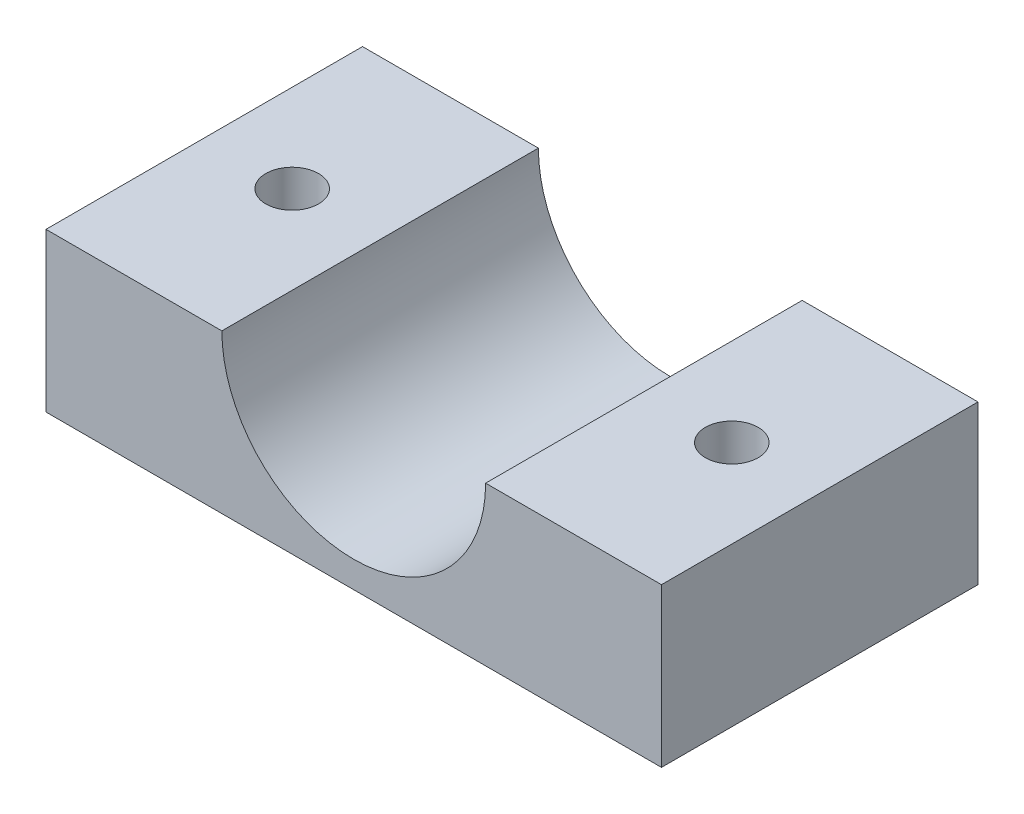
SolidWorks part; units mm, degrees
ref_plane "Front Plane" through (0, 0, 0) normal (0, 0, 1) x (1, 0, 0)
ref_plane "Top Plane" through (0, 0, 0) normal (0, 1, 0) x (1, 0, 0)
ref_plane "Right Plane" through (0, 0, 0) normal (1, 0, 0) x (0, 0, -1)
sketch "Sketch1" plane through (0, 0, 0) normal (0, 1, 0) x (1, 0, 0)
  line L0 (0, -1000) -> (0, 49000) construction
  line L1 (-17.5, -9) -> (17.5, -9)
  line L2 (-17.5, -9) -> (-17.5, 9)
  line L3 (-17.5, 9) -> (17.5, 9)
  line L4 (17.5, -9) -> (17.5, 9)
  line L5 (-17.5, -9) -> (17.5, 9) construction
  line L6 (-17.5, 9) -> (17.5, -9) construction
  line L7 (-1000, 0) -> (49000, 0) construction
  line L8 (7.5, -1000) -> (7.5, 49000) construction
  line L9 (-7.5, -1000) -> (-7.5, 49000) construction
  circle A0 centre (-12.5, 0) radius 1.5
  circle A1 centre (12.5, 0) radius 1.5
  point P0 (0, 0)
  dimension "D4" = 3
  dimension "D1" = 18
  dimension "D2" = 35
  dimension "D3" = 5
  dimension "D5" = 7.5
  dimension "D6" = 7.5
extrude "Boss-Extrude1" add sketch "Sketch1" along normal blind 9
sketch "Sketch2" plane through (0, 0, 9) normal (0, 0, 1) x (1, 0, 0)
  line L0 (0, -999.8574) -> (0, 49000.1426) construction
  line L1 (-17.5, 9) -> (17.5, 9) construction
  circle A0 centre (0, 9) radius 7.5
  dimension "D1" = 15
extrude "Cut-Extrude1" cut sketch "Sketch2" against normal up to next
